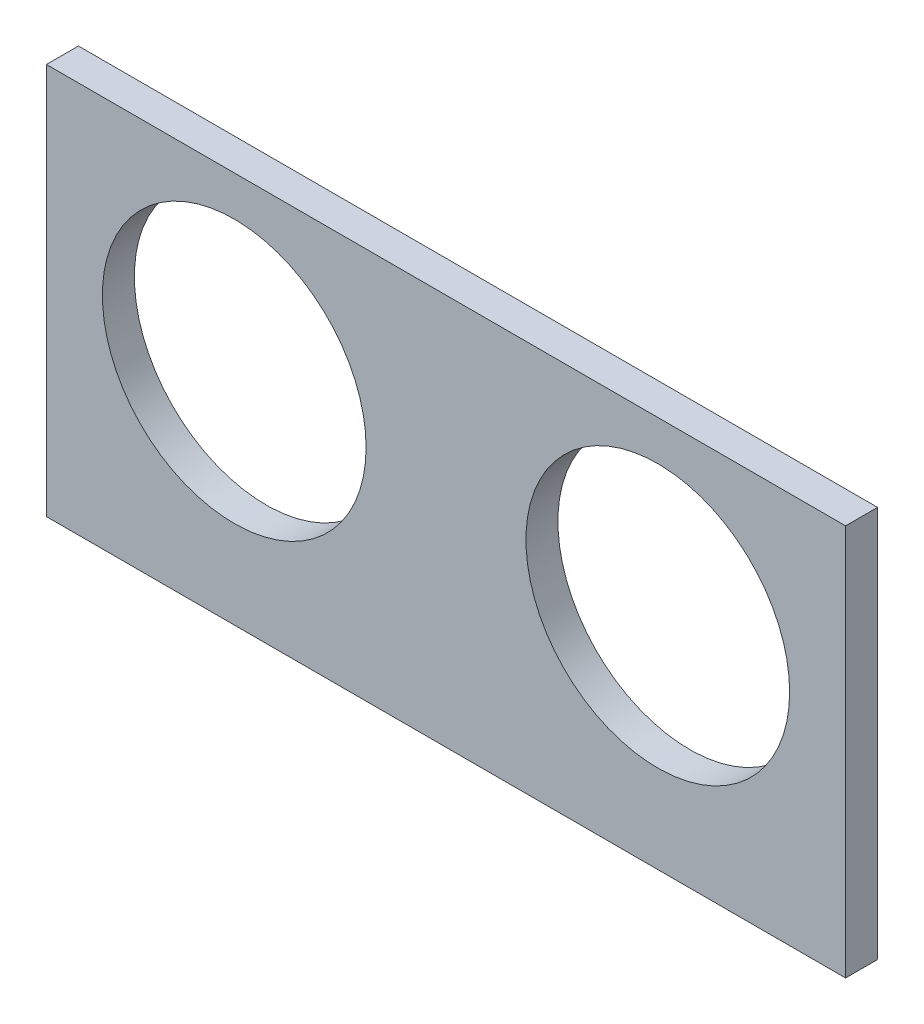
SolidWorks part; units mm, degrees
ref_plane "Front Plane" through (0, 0, 0) normal (0, 0, 1) x (1, 0, 0)
ref_plane "Top Plane" through (0, 0, 0) normal (0, 1, 0) x (1, 0, 0)
ref_plane "Right Plane" through (0, 0, 0) normal (1, 0, 0) x (0, 0, -1)
sketch "Sketch1" plane through (0, 0, 0) normal (0, 0, 1) x (1, 0, 0)
  line L0 (0, 22.5) -> (0, 0)
  line L1 (0, 0) -> (50, 0)
  line L2 (50, 0) -> (50, 22.5)
  line L3 (50, 22.5) -> (0, 22.5)
  dimension "D1" = 50
  dimension "D2" = 22.5
extrude "Boss-Extrude1" add sketch "Sketch1" along normal blind 2
sketch "Sketch2" plane through (0, 0, 2) normal (0, 0, 1) x (1, 0, 0)
  line L0 (0, 11.25) -> (50, 11.25) construction
  line L1 (3.5, 13.75) -> (3.5, 17.1241) construction
  line L2 (46.5, 13.75) -> (46.5, 17.5569) construction
  line L3 (0, 13.75) -> (50, 13.75) construction
  line L4 (38.25, 22) -> (40.5547, 22) construction
  line L5 (38.25, 5.5) -> (43.9599, 5.5) construction
  line L6 (0, 22.5) -> (0, 0) construction
  line L7 (50, 0) -> (50, 22.5) construction
  circle A0 centre (11.75, 13.75) radius 8.25
  circle A1 centre (38.25, 13.75) radius 8.25
  dimension "D1" = 16.5
  dimension "D3" = 3.5
  dimension "D2" = 2.5
  dimension "D4" = 3.5
extrude "Cut-Extrude1" cut sketch "Sketch2" against normal blind 2
sketch "Sketch3" plane through (0, 22.5, 0) normal (0, 1, 0) x (1, 0, 0)
  line L1 (0, 0) -> (50, 0)
  line L2 (0, 0) -> (0, -2)
  line L3 (0, -2) -> (50, -2)
  line L4 (50, 0) -> (50, -2)
extrude "Boss-Extrude2" add sketch "Sketch3" along normal blind 2
